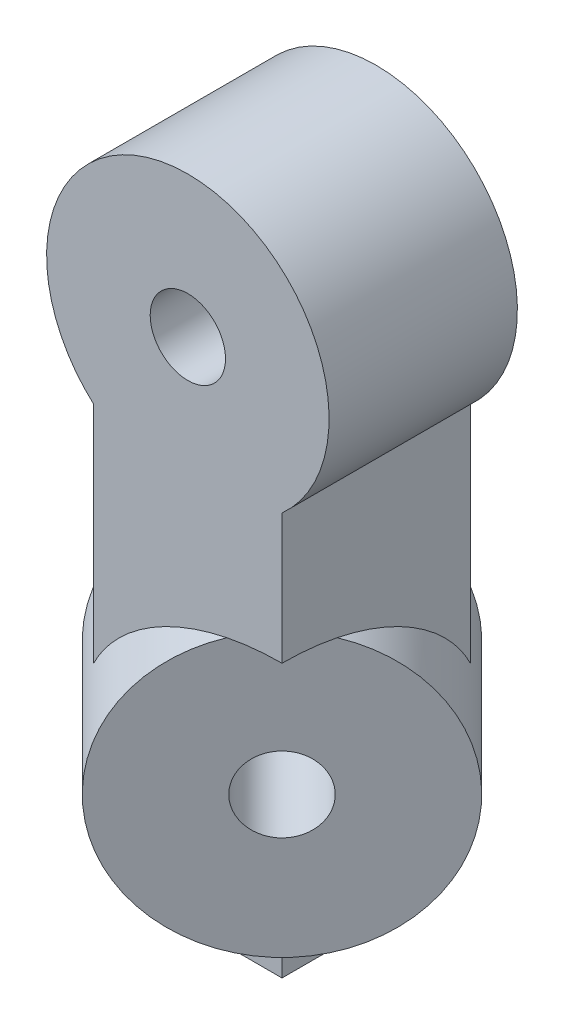
SolidWorks part; units mm, degrees
material "PLA"
ref_plane "Front Plane" through (0, 0, 0) normal (0, 0, 1) x (1, 0, 0)
ref_plane "Top Plane" through (0, 0, 0) normal (0, 1, 0) x (1, 0, 0)
ref_plane "Right Plane" through (0, 0, 0) normal (1, 0, 0) x (0, 0, -1)
sketch "Sketch1" plane through (0, 0, 0) normal (0, 0, 1) x (1, 0, 0)
  line L1 (5.0265, -10.0235) -> (-4.9735, -10.0235)
  line L2 (5.0265, -10.0235) -> (5.0265, 4.3863)
  line L4 (-4.9735, -10.0235) -> (-4.9735, 4.3863)
  line L5 (5.0265, -10.0235) -> (-1.3013, 2.5949) construction
  line L6 (1.288, 2.5958) -> (-4.9735, -10.0235) construction
  arc A0 (5.0265, 4.3863) -> (-4.9735, 4.3863) centre (0.0265, 9.9765) ccw
  circle A1 centre (0.0265, 9.9765) radius 1.5
  point P0 (0, 0)
  dimension "D2" = 15
  dimension "D3" = 3
  dimension "D1" = 10
  dimension "D4" = 20
extrude "Boss-Extrude1" add sketch "Sketch1" along normal blind 10
sketch "Sketch2" plane through (0, 0, 0) normal (0, 0, -1) x (-1, 0, 0)
  circle A0 centre (-0.0265, 9.9765) radius 2
  dimension "D1" = 4
extrude "Cut-Extrude1" cut sketch "Sketch2" against normal blind 30 contours A0
ref_plane "Plane1" through (2.5132, 0, 2.5132) normal (-0.7071, 0, -0.7071) x (-0.7071, 0, 0.7071)
sketch "Sketch6" plane through (2.5132, 0, 2.5132) normal (-0.7071, 0, -0.7071) x (-0.7071, 0, 0.7071)
  circle A0 centre (3.5168, -10.0235) radius 7.5
  dimension "D1" = 15
extrude "Boss-Extrude3" add sketch "Sketch6" along normal mid plane 10
sketch "Sketch7" plane through (-1.0223, 0, -1.0223) normal (-0.7071, 0, -0.7071) x (-0.7071, 0, 0.7071)
  line L0 (1.4458, -10.0235) -> (5.5879, -10.0235) construction
  circle A0 centre (3.5168, -10.0235) radius 1.5
  dimension "D1" = 3
extrude "Cut-Extrude4" cut sketch "Sketch7" against normal through all both and the other way through all
sketch "Sketch8" plane through (-1.0223, 0, -1.0223) normal (-0.7071, 0, -0.7071) x (-0.7071, 0, 0.7071)
  circle A0 centre (3.5168, -10.0235) radius 2
  dimension "D1" = 4
extrude "Cut-Extrude5" cut sketch "Sketch8" against normal mid plane 36
sketch "Sketch10" plane through (6.0488, 0, 6.0488) normal (0.7071, 0, 0.7071) x (0.7071, 0, -0.7071)
  circle A0 centre (-3.5168, -10.0235) radius 7.5
extrude "Cut-Extrude7" cut sketch "Sketch10" along normal blind 9
mirror "Mirror1" about plane through (2.5132, 0, 2.5132) normal (-0.7071, 0, -0.7071) of "Cut-Extrude7"
ref_plane "Plane2" through (0, -17.5, 0) normal (0, 1, 0) x (1, 0, 0)
sketch "Sketch11" plane through (0, -17.5, 0) normal (0, 1, 0) x (1, 0, 0)
  line L0 (-5.2768, -10.3033) -> (5.3298, 0.3033) construction
  line L1 (-8.8124, -6.7678) -> (-1.7413, -13.8388) construction
  line L2 (8.8653, -3.2322) -> (1.7942, 3.8388) construction
  line L4 (2.0265, -3) -> (-1.9735, -3)
  line L5 (2.0265, -3) -> (2.0265, -7)
  line L6 (2.0265, -7) -> (-1.9735, -7)
  line L7 (-1.9735, -3) -> (-1.9735, -7)
  line L8 (2.0265, -3) -> (-1.9735, -7) construction
  line L9 (2.0265, -7) -> (-1.9735, -3) construction
  point P6 (0.0265, -5)
  dimension "D1" = 4
extrude "Boss-Extrude4" add sketch "Sketch11" along normal mid plane 5
